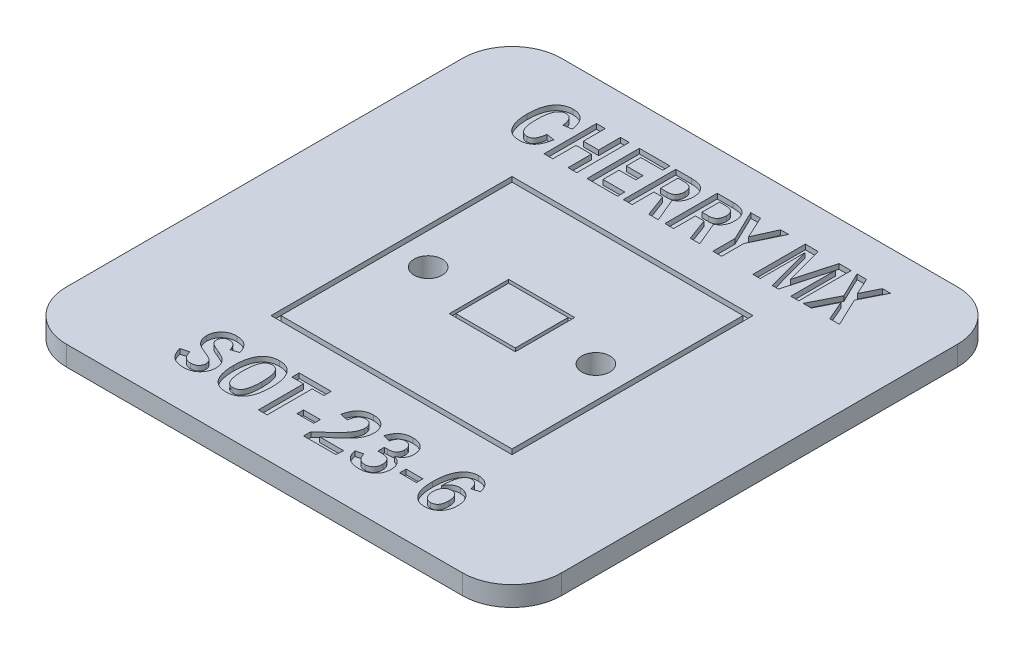
SolidWorks part; units mm, degrees
ref_plane "Front Plane" through (0, 0, 0) normal (0, 0, 1) x (1, 0, 0)
ref_plane "Top Plane" through (0, 0, 0) normal (0, 1, 0) x (1, 0, 0)
ref_plane "Right Plane" through (0, 0, 0) normal (1, 0, 0) x (0, 0, -1)
sketch "Sketch1" plane through (0, 0, 0) normal (0, 1, 0) x (1, 0, 0)
  line L1 (15, -15) -> (-15, -15)
  line L2 (15, -15) -> (15, 15)
  line L3 (15, 15) -> (-15, 15)
  line L4 (-15, -15) -> (-15, 15)
  line L5 (15, -15) -> (-15, 15) construction
  line L6 (15, 15) -> (-15, -15) construction
  point P0 (0, 0)
  dimension "D1" = 30
  dimension "D2" = 30
extrude "Boss-Extrude1" add sketch "Sketch1" against normal blind 1.2
sketch "Sketch2" plane through (0, 0, 0) normal (0, 1, 0) x (1, 0, 0)
  line L0 (-5.08, 0) -> (5.08, 0) construction
  circle A0 centre (-5.08, 0) radius 0.85
  circle A1 centre (5.08, 0) radius 0.85
  dimension "D2" = 1.7
  dimension "D1" = 10.16
extrude "Cut-Extrude1" cut sketch "Sketch2" against normal through all
sketch "Sketch7" plane through (0, 0, 0) normal (0, 1, 0) x (1, 0, 0)
  line L1 (7, -7) -> (-7, -7)
  line L2 (7, -7) -> (7, 7)
  line L3 (7, 7) -> (-7, 7)
  line L4 (-7, -7) -> (-7, 7)
  line L5 (7, -7) -> (-7, 7) construction
  line L6 (7, 7) -> (-7, -7) construction
  point P0 (0, 0)
  dimension "D1" = 14
  dimension "D2" = 14
extrude "Cut-Extrude-Thin1" cut sketch "Sketch7" against normal blind 0.3 thin thin type one direction wall 0.3
sketch "Sketch8" plane through (0, 0, 0) normal (0, 1, 0) x (1, 0, 0)
  line L0 (-15, -12.6297) -> (15, -12.6297) construction
  line L1 (15, -15) -> (15, 15) construction
  line L2 (-15, 15) -> (-15, -15) construction
  line L3 (-15, 9.461) -> (15, 9.461) construction
  text T0 "SOT-23-6" font "Franklin Gothic Medium Cond" height 3.175
  text T1 "CHERRY MX" font "Franklin Gothic Medium Cond" height 3.175
  point P8 (15, -12.1213)
extrude "Cut-Extrude2" cut sketch "Sketch8" against normal blind 0.3
sketch "Sketch9" plane through (0, 0, 0) normal (0, 1, 0) x (1, 0, 0)
  line L1 (-1.8, -1.6) -> (1.8, -1.6)
  line L2 (-1.8, -1.6) -> (-1.8, 1.6)
  line L3 (-1.8, 1.6) -> (1.8, 1.6)
  line L4 (1.8, -1.6) -> (1.8, 1.6)
  line L5 (-1.8, -1.6) -> (1.8, 1.6) construction
  line L6 (-1.8, 1.6) -> (1.8, -1.6) construction
  point P0 (0, 0)
  dimension "D1" = 3.6
  dimension "D2" = 3.2
extrude "Cut-Extrude-Thin2" cut sketch "Sketch9" against normal blind 0.2 thin
sketch "Sketch4" plane through (0, 0, 0) normal (0, 1, 0) x (1, 0, 0)
  line L1 (-1.45, -0.8) -> (1.45, -0.8)
  line L2 (-1.45, -0.8) -> (-1.45, 0.8)
  line L3 (-1.45, 0.8) -> (1.45, 0.8)
  line L4 (1.45, -0.8) -> (1.45, 0.8)
  line L5 (-1.45, -0.8) -> (1.45, 0.8) construction
  line L6 (-1.45, 0.8) -> (1.45, -0.8) construction
  point P0 (0, 0)
  dimension "D1" = 2.9
  dimension "D2" = 1.6
extrude "Boss-Extrude2" [suppressed] add sketch "Sketch4" along normal blind 1.2
ref_plane "Plane1" through (0, 0.8, 0) normal (0, 1, 0) x (1, 0, 0)
split line "Split Line1" [suppressed]
fillet "Fillet1" radius 3 4 edges at (-15, -0.6, 15) (15, -0.6, -15) (-15, -0.6, -15) (15, -0.6, 15)
draft "Draft1" [suppressed] type of draft neutral plane draft angle 10 neutral plane "Plane1" faces to draft 4 parameters "D1"=10
draft "Draft2" [suppressed] type of draft neutral plane draft angle 10 neutral plane "Plane1" faces to draft 4 parameters "D1"=10
sketch "Sketch5" plane through (0, 0, 0) normal (1, 0, 0) x (0, 0, -1)
  line L0 (0, 0.75) -> (-0.8, 0.75)
  line L1 (-0.9415, 0.6498) -> (-1.1085, 0.1752)
  line L2 (-1.25, 0.075) -> (-1.45, 0.075)
  line L3 (0, 0) -> (0, 0.75) construction
  arc A0 (-0.8, 0.75) -> (-0.9415, 0.6498) centre (-0.8, 0.6) ccw
  arc A1 (-1.1085, 0.1752) -> (-1.25, 0.075) centre (-1.25, 0.225) cw
  point P7 (-0.7156, 0.75)
  point P11 (-0.8081, 0.75)
  point P12 (0, 0)
  point P13 (0, 0)
  point P14 (-1.25, 0)
  point P15 (-1.25, -0.1293)
  point P16 (-1.25, 0.1922)
  point P17 (0, 0)
  dimension "D1" = 0.15
  dimension "D2" = 0.2
  dimension "D3" = 0.75
  dimension "D4" = 2.9
  dimension "D5" = 0.075
extrude "Extrude-Thin1" [suppressed] add sketch "Sketch5" along normal mid plane 0.4 thin
pattern_linear "LPattern1" [suppressed] count 2 spacing 0.95 count 2 spacing 0.95
mirror "Mirror1" [suppressed] about plane through (0, 0, 0) normal (0, 0, 1)
